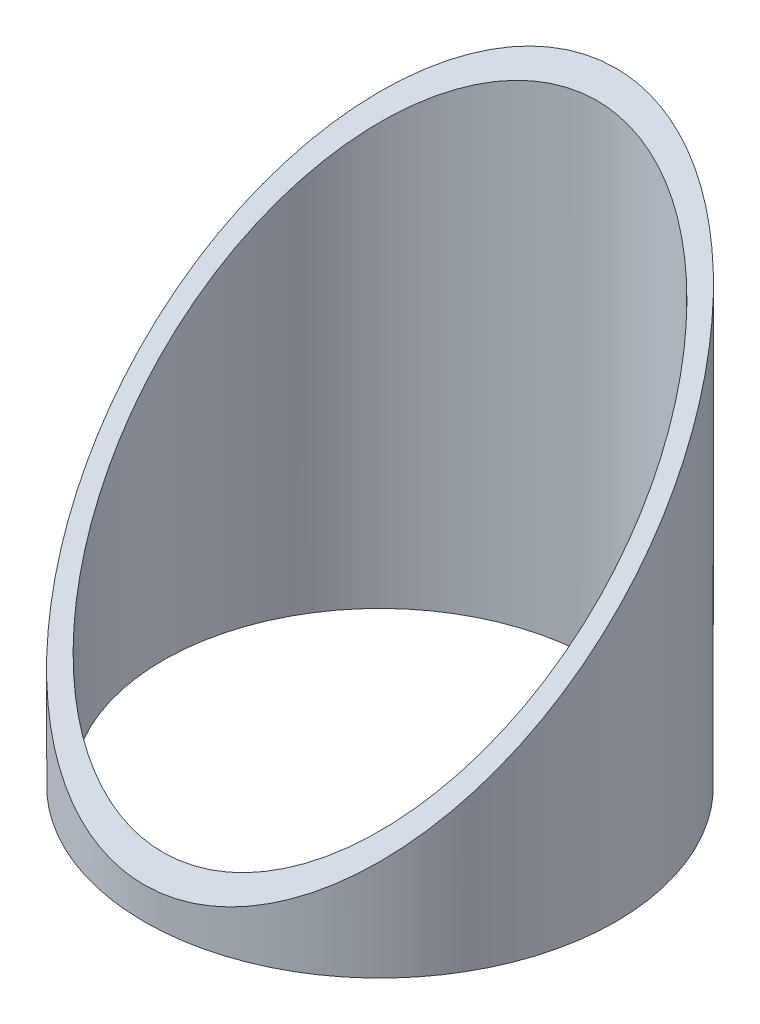
SolidWorks part; units mm, degrees
material "1060 Alloy"
ref_plane "Front Plane" through (0, 0, 0) normal (0, 0, 1) x (1, 0, 0)
ref_plane "Top Plane" through (0, 0, 0) normal (0, 1, 0) x (1, 0, 0)
ref_plane "Right Plane" through (0, 0, 0) normal (1, 0, 0) x (0, 0, -1)
sketch "Sketch1" plane through (0, 0, 0) normal (0, 1, 0) x (1, 0, 0)
  line L0 (-102.6662, 0) -> (114.9528, 0) construction
  line L1 (-55, 0) -> (55, 0) construction
ref_plane "Plane1" through (0, 0, 0) normal (0, 0.7071, 0.7071) x (1, 0, 0)
sketch "Sketch2" plane through (0, 0, 0) normal (0, 0.7071, 0.7071) x (1, 0, 0)
  circle A0 centre (0, 20) radius 20
  dimension "D1" = 40
extrude "Boss-Extrude1" add sketch "Sketch2" against normal blind 0.7071
ref_plane "Plane2" through (0, -3.25, 0) normal (0, 1, 0) x (1, 0, 0)
sketch "Sketch3" plane through (0, -3.25, 0) normal (0, 1, 0) x (1, 0, 0)
  line L0 (0, -15.8313) -> (0, 15.8313) construction
  circle A0 centre (0, 7.4) radius 7.4
  circle A1 centre (0, 7.4) radius 5.9
  dimension "D1" = 14.8
  dimension "D2" = 11.8
extrude "Boss-Extrude2" add sketch "Sketch3" along normal blind 1 separate body
sketch "Sketch4" plane through (0, -3.25, 0) normal (0, -1, 0) x (1, 0, 0)
  line L1 (-145.8552, 47.5561) -> (159.3648, 47.5561)
  line L2 (-145.8552, 47.5561) -> (-145.8552, -79.3149)
  line L3 (-145.8552, -79.3149) -> (159.3648, -79.3149)
  line L4 (159.3648, 47.5561) -> (159.3648, -79.3149)
  circle A3 centre (0, -7.4) radius 6.4
  circle A4 centre (0, -7.4) radius 7.4 construction
  dimension "D1" = 12.8
  dimension "D2" = 0
extrude "Cut-Extrude1" cut sketch "Sketch4" against normal through all both and the other way through all
sketch "Sketch5" plane through (0, -2.25, 0) normal (0, 1, 0) x (1, 0, 0)
  circle A1 centre (0, 7.4) radius 6.28
  circle A2 centre (0, 7.4) radius 7.4 construction
  circle A3 centre (0, 7.4) radius 5.78
  dimension "D1" = 12.56
  dimension "D3" = 11.56
  dimension "D2" = 0
extrude "Boss-Extrude3" add sketch "Sketch5" along normal up to next separate body
sketch "Sketch7" plane through (0, 0, 0) normal (0, 0.7071, 0.7071) x (1, 0, 0)
  circle A0 centre (0, 10.4652) radius 18.2827
extrude "Cut-Extrude3" cut sketch "Sketch7" against normal up to surface (0.7071 mm away) up to face at (0, 0, -1)
sketch "Sketch8" plane through (0, -3.25, 0) normal (0, -1, 0) x (1, 0, 0)
  circle A0 centre (0, -7.3953) radius 12.7728
extrude "Cut-Extrude4" cut sketch "Sketch8" against normal blind 2.52
